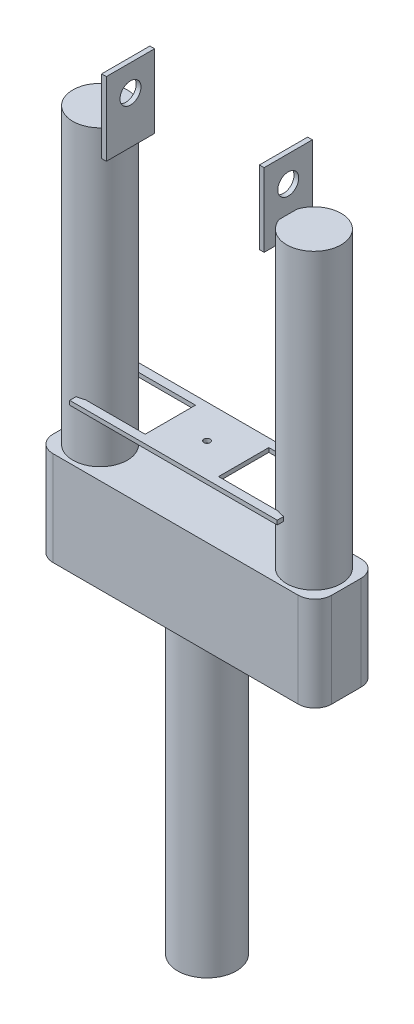
SolidWorks part; units mm, degrees
ref_plane "Front Plane" through (0, 0, 0) normal (0, 0, 1) x (1, 0, 0)
ref_plane "Top Plane" through (0, 0, 0) normal (0, 1, 0) x (1, 0, 0)
ref_plane "Right Plane" through (0, 0, 0) normal (1, 0, 0) x (0, 0, -1)
sketch "Sketch1" plane through (0, 0, 0) normal (0, 1, 0) x (1, 0, 0)
  circle A0 centre (0, 0) radius 14
  dimension "D1" = 28
extrude "Boss-Extrude1" add sketch "Sketch1" along normal blind 140
sketch "Sketch2" plane through (0, 140, 0) normal (0, 1, 0) x (1, 0, 0)
  line L0 (-66.5, 0) -> (-51, 0) construction
  line L1 (66.5, 15) -> (-66.5, 15)
  line L2 (66.5, 15) -> (66.5, -15)
  line L3 (66.5, -15) -> (-66.5, -15)
  line L4 (-66.5, 15) -> (-66.5, -15)
  line L5 (66.5, 15) -> (-66.5, -15) construction
  line L6 (66.5, -15) -> (-66.5, 15) construction
  line L7 (66.5, 0) -> (51, 0) construction
  point P0 (0, 0)
  dimension "D1" = 30
  dimension "D2" = 133
  dimension "D5" = 15.5
  dimension "D6" = 15.5
extrude "Boss-Extrude2" add sketch "Sketch2" along normal blind 45 contours L2 L1 L4 L3
sketch "Sketch3" plane through (0, 185, 0) normal (0, 1, 0) x (1, 0, 0)
  circle A0 centre (-51, 0) radius 13
  circle A1 centre (51, 0) radius 13
  dimension "D1" = 26
  dimension "D2" = 26
extrude "Boss-Extrude3" add sketch "Sketch3" along normal blind 140
fillet "Fillet1" radius 8 4 edges at (66.5, 162.5, 15) (66.5, 162.5, -15) (-66.5, 162.5, 15) (-66.5, 162.5, -15)
sketch "Sketch5" plane through (0, 325, 0) normal (0, 1, 0) x (1, 0, 0)
  line L0 (-38, 0) -> (-36.5, 0) construction
  line L1 (38, 0) -> (36.5, 0) construction
  line L2 (0, 0) -> (0, -23.814) construction
  line L3 (-36.5, 11.5) -> (-38.75, 11.5)
  line L4 (-36.5, 11.5) -> (-36.5, -11.5)
  line L5 (-36.5, -11.5) -> (-38.75, -11.5)
  line L6 (-38.75, 11.5) -> (-38.75, -11.5)
  line L7 (-36.5, 11.5) -> (-38.75, -11.5) construction
  line L8 (-36.5, -11.5) -> (-38.75, 11.5) construction
  line L9 (36.5, -11.5) -> (38.75, -11.5)
  line L10 (38.75, 11.5) -> (38.75, -11.5)
  line L11 (36.5, 11.5) -> (36.5, -11.5)
  line L12 (36.5, 11.5) -> (38.75, 11.5)
  circle A0 centre (-51, 0) radius 13 construction
  circle A1 centre (51, 0) radius 13 construction
  point P10 (-37.625, 0)
  point P24 (0, 0)
  dimension "D4" = 73
  dimension "D1" = 2.25
  dimension "D2" = 0.75
  dimension "D3" = 23
extrude "Boss-Extrude4" add sketch "Sketch5" along normal blind 35 from offset 10 offset against normal yes
sketch "Sketch6" plane through (-36.5, 0, 0) normal (1, 0, 0) x (0, 0, -1)
  line L0 (0, 350) -> (0, 337.5) construction
  line L1 (-11.5, 350) -> (11.5, 350) construction
  circle A0 centre (0, 337.5) radius 5
  dimension "D1" = 10
  dimension "D2" = 12.5
extrude "Cut-Extrude1" cut sketch "Sketch6" against normal through all both and the other way through all
sketch "Sketch7" plane through (0, 0, 15) normal (0, 0, 1) x (1, 0, 0)
  line L0 (-36.5, 350) -> (-36.5, 210) construction
sketch "Sketch8" plane through (0, 350, 0) normal (0, 1, 0) x (1, 0, 0)
  line L0 (0, 0) -> (0, -7.8877) construction
  line L1 (17.5, 16) -> (-17.5, 16)
  line L2 (17.5, 12) -> (17.5, -12)
  line L3 (17.5, -16) -> (-17.5, -16)
  line L4 (-17.5, 12) -> (-17.5, -12)
  line L5 (17.5, 16) -> (-17.5, -16) construction
  line L6 (17.5, -16) -> (-17.5, 16) construction
  line L7 (-17.5, 16) -> (-49.5, 16)
  line L9 (-17.5, 12) -> (-49.5, 12)
  line L10 (-49.5, 16) -> (-49.5, 12)
  line L11 (-17.5, 16) -> (-49.5, 12) construction
  line L12 (-17.5, 12) -> (-49.5, 16) construction
  line L13 (-17.5, -16) -> (-49.5, -16)
  line L15 (-17.5, -12) -> (-49.5, -12)
  line L16 (-49.5, -16) -> (-49.5, -12)
  line L17 (-17.5, -16) -> (-49.5, -12) construction
  line L18 (-17.5, -12) -> (-49.5, -16) construction
  line L19 (49.5, -16) -> (49.5, -12)
  line L20 (17.5, -16) -> (49.5, -16)
  line L21 (17.5, -12) -> (49.5, -12)
  line L22 (17.5, 12) -> (49.5, 12)
  line L23 (49.5, 16) -> (49.5, 12)
  line L24 (17.5, 16) -> (49.5, 16)
  point P0 (0, 0)
  point P9 (-33.5, 14)
  point P13 (-33.5, -14)
  dimension "D1" = 35
  dimension "D2" = 32
  dimension "D3" = 4
  dimension "D4" = 4
  dimension "D5" = 32
  dimension "D6" = 32
extrude "Boss-Extrude5" add sketch "Sketch8" along normal blind 2 from offset 140 offset against normal yes
sketch "Sketch9" plane through (0, 212, 0) normal (0, 1, 0) x (1, 0, 0)
  circle A0 centre (0, 0) radius 1.5
  dimension "D1" = 3
extrude "Cut-Extrude2" cut sketch "Sketch9" against normal up to next
sketch "Sketch10" plane through (0, 0, 0) normal (0, -1, 0) x (1, 0, 0)
  circle A0 centre (0, 0) radius 11
  dimension "D1" = 22
extrude "Cut-Extrude3" cut sketch "Sketch10" against normal blind 100
